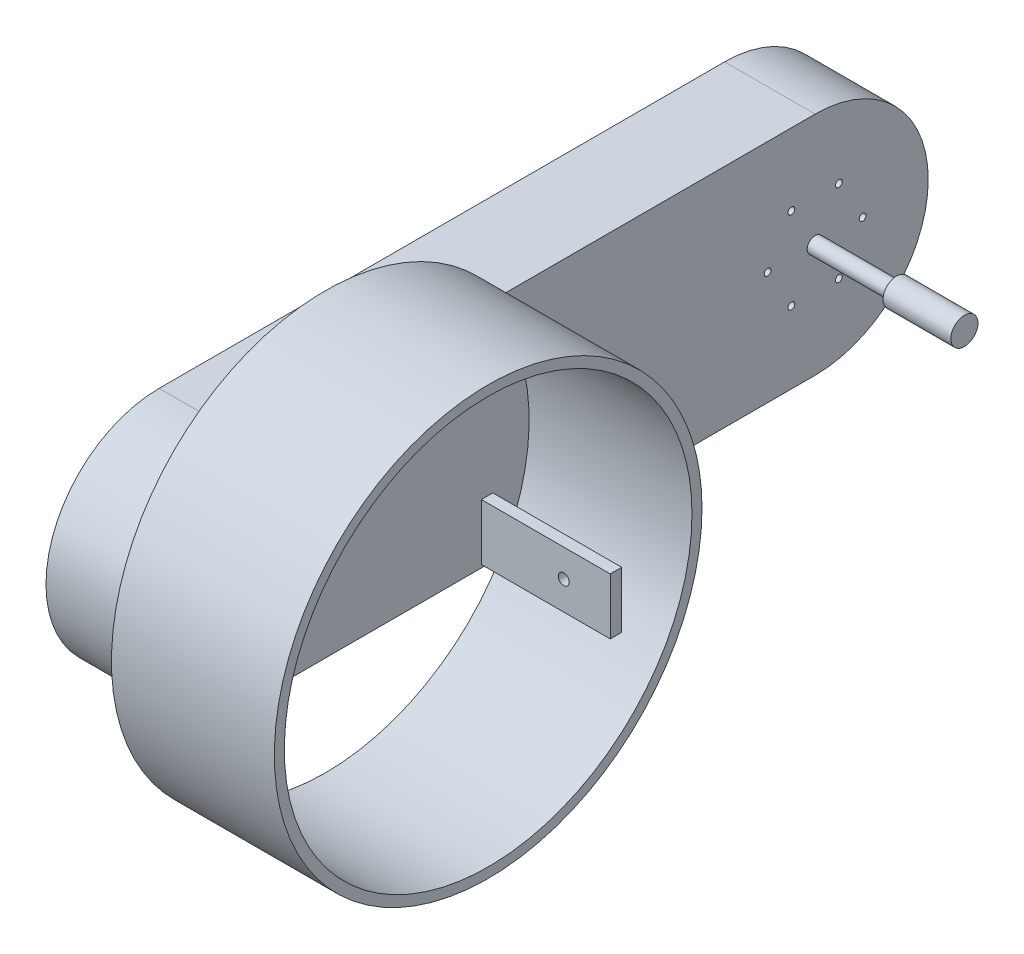
SolidWorks part; units mm, degrees
material "Cast Alloy Steel"
ref_plane "Front Plane" through (0, 0, 0) normal (0, 0, 1) x (1, 0, 0)
ref_plane "Top Plane" through (0, 0, 0) normal (0, 1, 0) x (1, 0, 0)
ref_plane "Right Plane" through (0, 0, 0) normal (1, 0, 0) x (0, 0, -1)
sketch "Sketch2" plane through (0, 0, 0) normal (1, 0, 0) x (0, 0, -1)
  line L0 (-7.709, -46.1404) -> (242.291, -46.1404)
  line L1 (242.291, -46.1404) -> (242.291, 53.8596)
  line L2 (242.291, 53.8596) -> (-7.709, 53.8596)
  line L3 (-7.709, 53.8596) -> (-7.709, -46.1404)
  circle A0 centre (-7.709, 3.8596) radius 50
  circle A1 centre (242.291, 3.8596) radius 50
  dimension "D1" = 250
  dimension "D2" = 100
extrude "Boss-Extrude1" add sketch "Sketch2" along normal blind 40 contours A1 L2 A0 L0 | L3 A0 | L3 A0 | L1 A1 | L1 A1
shell "Shell1" thickness 4
sketch "Sketch4" plane through (36, 0, 0) normal (-1, 0, 0) x (0, 0, 1)
  line L0 (-252.791, 22.0462) -> (-242.291, 3.8596)
  line L1 (-242.291, 3.8596) -> (-231.791, 22.0462)
  line L2 (-242.291, 3.8596) -> (-221.291, 3.8596)
  line L3 (-242.291, 3.8596) -> (-231.791, -14.3269)
  line L4 (-242.291, 3.8596) -> (-252.791, -14.3269)
  line L5 (-242.291, 3.8596) -> (-263.291, 3.8596)
  circle A0 centre (-242.291, 3.8596) radius 21
  circle A1 centre (-252.791, 22.0462) radius 1.5
  circle A2 centre (-231.791, 22.0462) radius 1.5
  circle A3 centre (-263.291, 3.8596) radius 1.5
  circle A4 centre (-221.291, 3.8596) radius 1.5
  circle A5 centre (-252.791, -14.3269) radius 1.5
  circle A6 centre (-231.791, -14.3269) radius 1.5
  dimension "D1" = 42
  dimension "D6" = 3
  dimension "D7" = 3
  dimension "D8" = 3
  dimension "D9" = 3
  dimension "D10" = 3
  dimension "D11" = 3
  dimension "D2" = 120
  dimension "D3" = 60
  dimension "D4" = 60
  dimension "D5" = 60
extrude "Cut-Extrude1" cut sketch "Sketch4" against normal blind 40 contours A2 | A4 | A6 | A5 | A3 | A1
sketch "Sketch6" plane through (36, 0, 0) normal (-1, 0, 0) x (0, 0, 1)
  circle A0 centre (-242.291, 3.8596) radius 3.5
  dimension "D1" = 7
extrude "Boss-Extrude2" add sketch "Sketch6" against normal blind 40
sketch "Sketch7" plane through (76, 0, 0) normal (1, 0, 0) x (0, 0, -1)
  circle A0 centre (242.291, 3.8596) radius 6
  dimension "D1" = 12
extrude "Boss-Extrude3" add sketch "Sketch7" along normal blind 30 contours A0
sketch "Sketch8" plane through (106, 0, 0) normal (1, 0, 0) x (0, 0, -1)
  point P0 (242.291, 3.8596)
sketch "Sketch9" plane through (40, 0, 0) normal (1, 0, 0) x (0, 0, -1)
  point P0 (242.291, 3.8596)
sketch "Sketch11" plane through (40, 0, 0) normal (1, 0, 0) x (0, 0, -1)
  circle A0 centre (0, 0) radius 7.6213
extrude "Cut-Extrude2" cut sketch "Sketch11" against normal blind 10
sketch "Sketch12" plane through (40, 0, 0) normal (1, 0, 0) x (0, 0, -1)
  line L0 (-7.709, -42.1404) -> (242.291, -42.1404) construction
  line L1 (71.6996, -22.1404) -> (75.5681, -22.1404)
  line L2 (71.6996, -22.1404) -> (71.6996, -42.1404)
  line L3 (71.6996, -42.1404) -> (75.5681, -42.1404)
  line L4 (75.5681, -22.1404) -> (75.5681, -42.1404)
  dimension "D1" = 20
sketch "Sketch14" plane through (40, 0, 0) normal (1, 0, 0) x (0, 0, -1)
  line L1 (94.7305, -19.9064) -> (99.8044, -19.9064)
  line L2 (94.7305, -19.9064) -> (94.7305, -44.7999)
  line L3 (94.7305, -44.7999) -> (99.8044, -44.7999)
  line L4 (99.8044, -19.9064) -> (99.8044, -44.7999)
extrude "Boss-Extrude5" add sketch "Sketch14" along normal blind 57
sketch "Sketch15" plane through (0, 0, -99.8044) normal (0, 0, -1) x (-1, 0, 0)
  circle A1 centre (-76.4309, -32.205) radius 2.4295
extrude "Cut-Extrude4" cut sketch "Sketch15" against normal blind 57
sketch "Sketch17" plane through (40, 0, 0) normal (1, 0, 0) x (0, 0, -1)
  line L0 (117.291, -46.1404) -> (117.291, 53.8596)
  line L1 (-7.709, -46.1404) -> (242.291, -46.1404) construction
  line L2 (242.291, 53.8596) -> (-7.709, 53.8596) construction
  line L3 (117.291, 53.8596) -> (-7.709, 53.8596)
  line L4 (117.291, -46.1404) -> (-7.709, -46.1404)
  arc A0 (-7.709, 53.8596) -> (-7.709, -46.1404) centre (-7.709, 3.8596) ccw construction
  arc A1 (-7.709, -46.1404) -> (-7.709, 53.8596) centre (-7.709, 3.8596) cw
sketch "Sketch18" plane through (40, 0, 0) normal (1, 0, 0) x (0, 0, -1)
  circle A0 centre (25.75, 0) radius 94.5247
  circle A1 centre (0, 0) radius 25.75 construction
  circle A2 centre (25.75, 0) radius 90.1076
extrude "Boss-Extrude7" add sketch "Sketch18" along normal blind 72
sketch "Sketch20" plane through (112, 0, 0) normal (1, 0, 0) x (0, 0, -1)
  circle A0 centre (5.2666, -19.178) radius 92.7157
  circle A1 centre (2.2102, -20.8834) radius 3.5 construction
